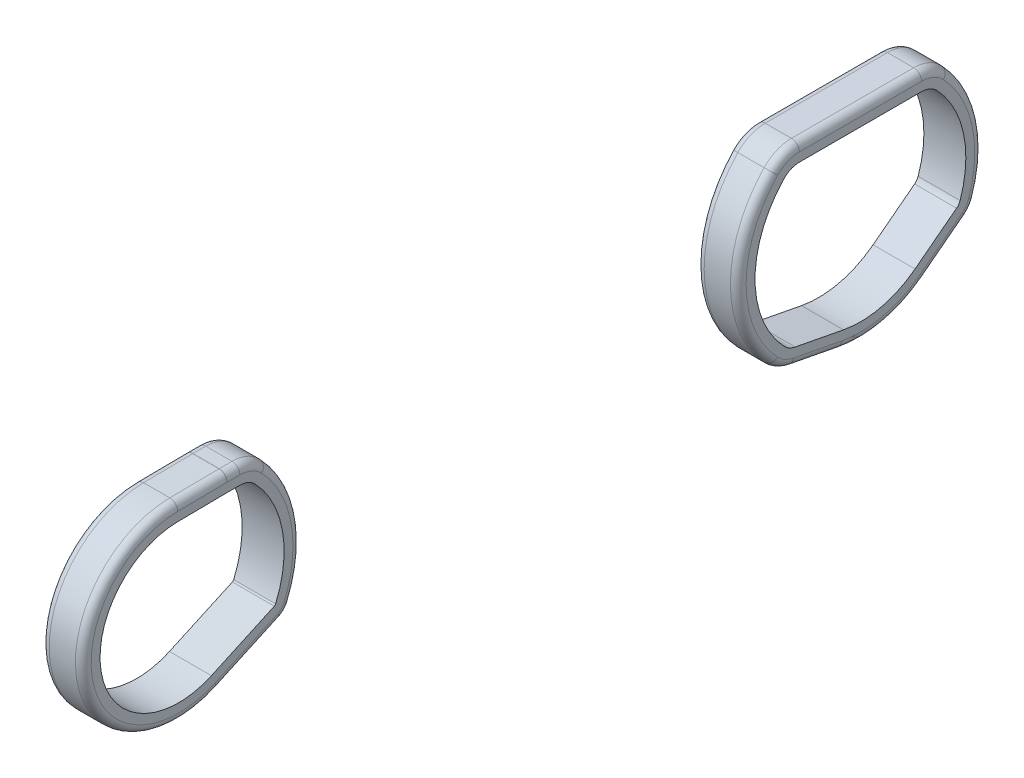
SolidWorks part; units mm, degrees
ref_plane "Front" through (0, 0, 0) normal (0, 0, 1) x (1, 0, 0)
ref_plane "Top" through (0, 0, 0) normal (0, 1, 0) x (1, 0, 0)
ref_plane "Right" through (0, 0, 0) normal (1, 0, 0) x (0, 0, -1)
sketch "Sketch1" plane through (0, 0, 0) normal (1, 0, 0) x (0, 0, -1)
  line L1 (40.667, -3.95) -> (41.0557, -3.95)
  line L3 (26.669, -7.55) -> (28.4875, -7.55)
  line L5 (27.8847, 7.55) -> (26.669, 7.55)
  line L7 (36.5144, 7.55) -> (36.021, 6.6221)
  line L8 (-32.5, 0) -> (32.5, 0) construction
  line L10 (38.331, 7.55) -> (36.5144, 7.55)
  line L12 (28.979, 6.6221) -> (28.7677, 7.0195)
  line L14 (-26.669, 7.55) -> (-27.8847, 7.55)
  line L16 (-26.1245, -3.95) -> (-23.2588, -3.95)
  line L18 (-28.7677, 7.0195) -> (-28.979, 6.6221)
  line L19 (28.979, 6.6221) -> (32.5, 0) construction
  line L20 (32.5, 0) -> (32.5, -8.55) construction
  line L21 (-32.5, 0) -> (-28.979, 6.6221) construction
  line L22 (-32.5, 0) -> (-32.5, -7.5) construction
  arc A1 (42.0011, -3.276) -> (39.7796, 6.9289) centre (32.5, 0) ccw
  arc A3 (41.0557, -3.95) -> (42.0011, -3.276) centre (41.0557, -2.95) ccw
  arc A5 (40.667, -3.95) -> (39.8118, -4.4317) centre (40.667, -4.95) ccw
  arc A7 (28.4875, -7.55) -> (39.8118, -4.4317) centre (32.5, 0) ccw
  arc A9 (25.2204, -6.9289) -> (26.669, -7.55) centre (26.669, -5.55) ccw
  arc A11 (25.2204, 6.9289) -> (25.2204, -6.9289) centre (32.5, 0) ccw
  arc A12 (36.021, 6.6221) -> (28.979, 6.6221) centre (32.5, 0) cw construction
  arc A17 (26.669, 7.55) -> (25.2204, 6.9289) centre (26.669, 5.55) ccw
  arc A19 (28.7677, 7.0195) -> (27.8847, 7.55) centre (27.8847, 6.55) ccw
  arc A21 (36.021, 6.6221) -> (28.979, 6.6221) centre (32.5, 0) ccw
  arc A23 (39.7796, 6.9289) -> (38.331, 7.55) centre (38.331, 5.55) ccw
  arc A27 (-28.979, 6.6221) -> (-26.1245, -3.95) centre (-32.5, 0) ccw
  arc A29 (-27.8847, 7.55) -> (-28.7677, 7.0195) centre (-27.8847, 6.55) ccw
  arc A31 (-23.2588, -3.95) -> (-25.2204, 6.9289) centre (-32.5, 0) ccw
  arc A33 (-25.2204, 6.9289) -> (-26.669, 7.55) centre (-26.669, 5.55) ccw
  point P8 (0, 0)
  dimension "D1" = 7.5
  dimension "D4" = 10.05
  dimension "D5" = 8.55
  dimension "D6" = 2
  dimension "D11" = 1
  dimension "D2" = 3.95
  dimension "D3" = 65
  dimension "D7" = 7.55
  dimension "D8" = 7.55
  dimension "D9" = 28
  dimension "D10" = 28
  dimension "D12" = 3.95
  dimension "D13" = 28
sketch "Sketch2" plane through (0, 0, 0) normal (1, 0, 0) x (0, 0, -1)
  line L0 (26.669, 7.55) -> (38.331, 7.55)
  line L1 (41.6647, -3.7432) -> (37.7066, -6.7819)
  line L2 (30.8877, -8.3966) -> (26.2919, -7.5141)
  line L3 (-26.669, 7.55) -> (-27.8847, 7.55) construction
  line L4 (-26.669, 7.55) -> (-27.8847, 7.55)
  line L5 (-32.5806, 7.4996) -> (-27.8955, 7.5499)
  line L6 (-29.3814, -6.8209) -> (-23.3847, -4.0791)
  line L7 (38.6809, -8.051) -> (42.639, -5.0123)
  line L8 (38.331, 9.15) -> (26.669, 9.15)
  line L9 (25.9902, -9.0854) -> (30.586, -9.9679)
  line L10 (-32.5978, 9.0995) -> (-27.9127, 9.1498)
  line L11 (-26.669, 9.15) -> (-27.8847, 9.15)
  line L12 (-28.7161, -8.276) -> (-22.7194, -5.5342)
  arc A0 (39.7796, 6.9289) -> (38.331, 7.55) centre (38.331, 5.55) ccw construction
  arc A1 (39.7796, 6.9289) -> (38.331, 7.55) centre (38.331, 5.55) ccw
  arc A2 (42.0011, -3.276) -> (39.7796, 6.9289) centre (32.5, 0) ccw construction
  arc A3 (42.0011, -3.276) -> (39.7796, 6.9289) centre (32.5, 0) ccw
  arc A4 (41.0557, -3.95) -> (42.0011, -3.276) centre (41.0557, -2.95) ccw construction
  arc A5 (41.6647, -3.7432) -> (42.0011, -3.276) centre (41.0557, -2.95) ccw
  arc A6 (28.4875, -7.55) -> (39.8118, -4.4317) centre (32.5, 0) ccw construction
  arc A7 (30.8877, -8.3966) -> (37.7066, -6.7819) centre (32.5, 0) ccw
  arc A8 (25.2204, -6.9289) -> (26.669, -7.55) centre (26.669, -5.55) ccw construction
  arc A9 (25.2204, -6.9289) -> (26.2919, -7.5141) centre (26.669, -5.55) ccw
  arc A10 (25.2204, 6.9289) -> (25.2204, -6.9289) centre (32.5, 0) ccw construction
  arc A11 (25.2204, 6.9289) -> (25.2204, -6.9289) centre (32.5, 0) ccw
  arc A12 (26.669, 7.55) -> (25.2204, 6.9289) centre (26.669, 5.55) ccw construction
  arc A13 (26.669, 7.55) -> (25.2204, 6.9289) centre (26.669, 5.55) ccw
  arc A14 (-23.2588, -3.95) -> (-25.2204, 6.9289) centre (-32.5, 0) ccw construction
  arc A15 (-23.2588, -3.95) -> (-25.2204, 6.9289) centre (-32.5, 0) ccw
  arc A16 (-25.2204, 6.9289) -> (-26.669, 7.55) centre (-26.669, 5.55) ccw construction
  arc A17 (-25.2204, 6.9289) -> (-26.669, 7.55) centre (-26.669, 5.55) ccw
  arc A18 (-28.979, 6.6221) -> (-26.1245, -3.95) centre (-32.5, 0) ccw construction
  arc A19 (-32.5806, 7.4996) -> (-29.3814, -6.8209) centre (-32.5, 0) ccw
  arc A20 (-27.8847, 7.55) -> (-28.7677, 7.0195) centre (-27.8847, 6.55) ccw construction
  arc A21 (-27.8847, 7.55) -> (-27.8955, 7.5499) centre (-27.8847, 6.55) ccw
  arc A22 (-23.3847, -4.0791) -> (-23.2588, -3.95) centre (-23.4887, -3.8517) ccw
  arc A23 (30.586, -9.9679) -> (38.6809, -8.051) centre (32.5, 0) ccw
  arc A24 (28.979, 6.6221) -> (36.021, 6.6221) centre (32.5, 0) ccw construction
  arc A25 (42.639, -5.0123) -> (43.5137, -3.7975) centre (41.0557, -2.95) ccw
  arc A26 (43.5137, -3.7975) -> (40.9386, 8.032) centre (32.5, 0) ccw
  arc A27 (40.9386, 8.032) -> (38.331, 9.15) centre (38.331, 5.55) ccw
  arc A28 (26.669, 9.15) -> (24.0614, 8.032) centre (26.669, 5.55) ccw
  arc A29 (24.0614, 8.032) -> (24.0614, -8.032) centre (32.5, 0) ccw
  arc A30 (24.0614, -8.032) -> (25.9902, -9.0854) centre (26.669, -5.55) ccw
  arc A31 (-27.8847, 9.15) -> (-27.9127, 9.1498) centre (-27.8847, 6.55) ccw
  arc A32 (-24.0614, 8.032) -> (-26.669, 9.15) centre (-26.669, 5.55) ccw
  arc A33 (-21.7876, -4.5789) -> (-24.0614, 8.032) centre (-32.5, 0) ccw
  arc A34 (-22.7194, -5.5342) -> (-21.7876, -4.5789) centre (-23.4887, -3.8517) ccw
  arc A35 (-32.5978, 9.0995) -> (-28.7161, -8.276) centre (-32.5, 0) ccw
  dimension "D1" = 0.25
  dimension "D2" = 2.65
  dimension "D3" = 1.6
extrude "Boss-Extrude1" add sketch "Sketch2" along normal mid plane 4
fillet "Fillet1" radius 0.75 20 edges at (-2, 8.8587, -39.7496) (-2, 2.478, -43.8834) (-2, -4.4692, -43.1657) (-2, -6.5317, -40.6599) (-2, -9.8769, -34.8388) (-2, -9.5267, -28.2881) (-2, -8.7095, -24.9434) (-2, 0, -20.85) (-2, 8.8587, -25.2504) (2, 8.8587, -39.7496) (2, 2.478, -43.8834) (2, -4.4692, -43.1657) (2, -6.5317, -40.6599) (2, -9.8769, -34.8388) (2, -9.5267, -28.2881) (2, -8.7095, -24.9434) (2, 0, -20.85) (2, 8.8587, -25.2504) (-2, 9.15, -32.5) (2, 9.15, -32.5)
fillet "Fillet2" radius 0.75 16 edges at (-2, 9.15, 27.8987) (-2, 9.15, 27.2769) (-2, 8.8587, 25.2504) (-2, 2.0673, 21.0349) (-2, -5.1435, 22.1643) (-2, -6.9051, 25.7178) (-2, -1.9841, 41.3811) (2, 9.15, 27.8987) (2, 9.15, 27.2769) (2, 8.8587, 25.2504) (2, 2.0673, 21.0349) (2, -5.1435, 22.1643) (2, -6.9051, 25.7178) (2, -1.9841, 41.3811) (-2, 9.1247, 30.2553) (2, 9.1247, 30.2553)
